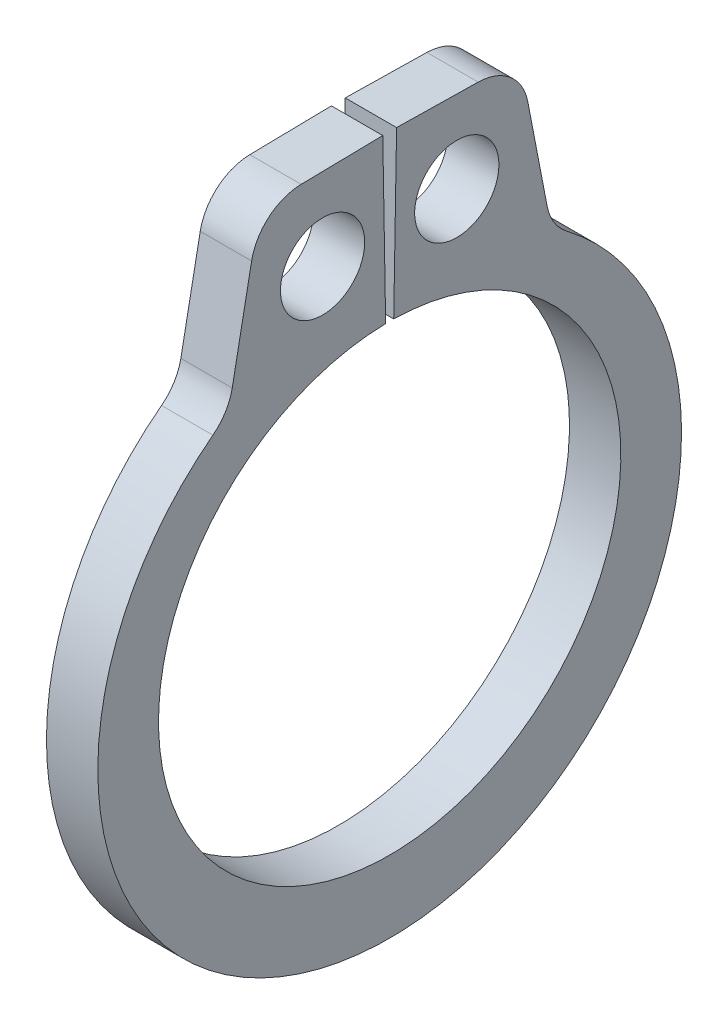
SolidWorks part; units mm, degrees
material "Cast Carbon Steel"
ref_plane "Front" through (0, 0, 0) normal (0, 0, 1) x (1, 0, 0)
ref_plane "Top" through (0, 0, 0) normal (0, 1, 0) x (1, 0, 0)
ref_plane "Right" through (0, 0, 0) normal (1, 0, 0) x (0, 0, -1)
sketch "Sketch1" plane through (0, 0, 0) normal (1, 0, 0) x (0, 0, -1)
  line L0 (0, 0) -> (0, 2.8575) construction
  line L1 (-0.0499, 2.8571) -> (-0.0853, 4.8888)
  line L2 (0.0853, 4.8888) -> (1.6091, 4.8622)
  line L3 (1.6091, 4.8622) -> (1.9944, 2.867)
  line L4 (0.0499, 2.8571) -> (0.0853, 4.8888)
  line L5 (-0.0853, 4.8888) -> (-1.6091, 4.8622)
  line L6 (-1.6091, 4.8622) -> (-1.9944, 2.867)
  line L7 (-1.9944, 2.867) -> (-1.6318, 2.3457) construction
  line L8 (1.9944, 2.867) -> (1.6318, 2.3457) construction
  line L9 (0, -2.8575) -> (0, -3.7465) construction
  line L10 (-1.6091, 4.8622) -> (-0.0499, 2.8571) construction
  line L11 (0, 2.8575) -> (0, 4.8895) construction
  line L12 (-2.8575, 0) -> (2.8575, 0) construction
  circle A0 centre (0, 0) radius 2.8575 construction
  arc A1 (-0.0499, 2.8571) -> (0.0499, 2.8571) centre (0, 0) ccw
  circle A3 centre (0, 0) radius 5.715 construction
  circle A4 centre (-0.8295, 3.8596) radius 0.5207
  circle A5 centre (0.8295, 3.8596) radius 0.5207
  arc A6 (-1.9944, 2.867) -> (1.9944, 2.867) centre (0, -0.139) ccw
  point P0 (0, -3.7465)
  dimension "A" = 5.715
  dimension "Hole" = 1.0414
  dimension "Smin" = 0.635
  dimension "H" = 2.032
  dimension "D2" = 1.524
  dimension "Angle" = 1
extrude "Extrude1" add sketch "Sketch1" along normal mid plane 0.635
fillet "Fillet1" radius 0.635 4 edges at (0, 2.867, 1.9944) (0, 2.867, -1.9944) (0, 4.8622, 1.6091) (0, 4.8622, -1.6091)
sketch "Sketch2" plane through (0, 0, 0) normal (0, 0, 1) x (1, 0, 0)
  line L0 (-3.5433, 0) -> (9.1567, 0)
  line L1 (9.1567, 0) -> (9.1567, -3.175)
  line L2 (-3.5433, 0) -> (-3.5433, -2.921)
  line L3 (9.1567, -3.175) -> (0.3683, -3.175)
  line L4 (0.3683, -3.175) -> (0.3683, -2.921)
  line L5 (0.3683, -2.921) -> (-0.3683, -2.921)
  line L6 (-0.3683, -2.921) -> (-0.3683, -3.175)
  line L7 (-0.3683, -3.175) -> (-3.5433, -3.175) construction
  line L8 (-3.5433, -3.175) -> (-3.5433, 0) construction
  line L9 (9.1567, 0) -> (76.391, 0) construction
  line L10 (0, -2.921) -> (0, 0) construction
  line L11 (-3.5433, -2.921) -> (-3.2893, -3.175)
  line L12 (-3.2893, -3.175) -> (-0.3683, -3.175)
  dimension "D2" = 12.7
  dimension "D3" = 3.175
  dimension "D1" = 45
revolve "Revolve1" [suppressed] add sketch "Sketch2" angle 360 about L9
delete or keep bodies "Body-Delete1" [suppressed] type delete bodies bodies 122
equation "\"D2@Sketch2\" = \"D1@Extrude1\"*20"
equation "\"D3@Sketch2\" = \"D2@Sketch2\"/4"
equation "\"D2@Sketch1\" = \"H@Sketch1\"*.75"
equation "\"D1@Fillet1\" = \"D1@Extrude1\""
